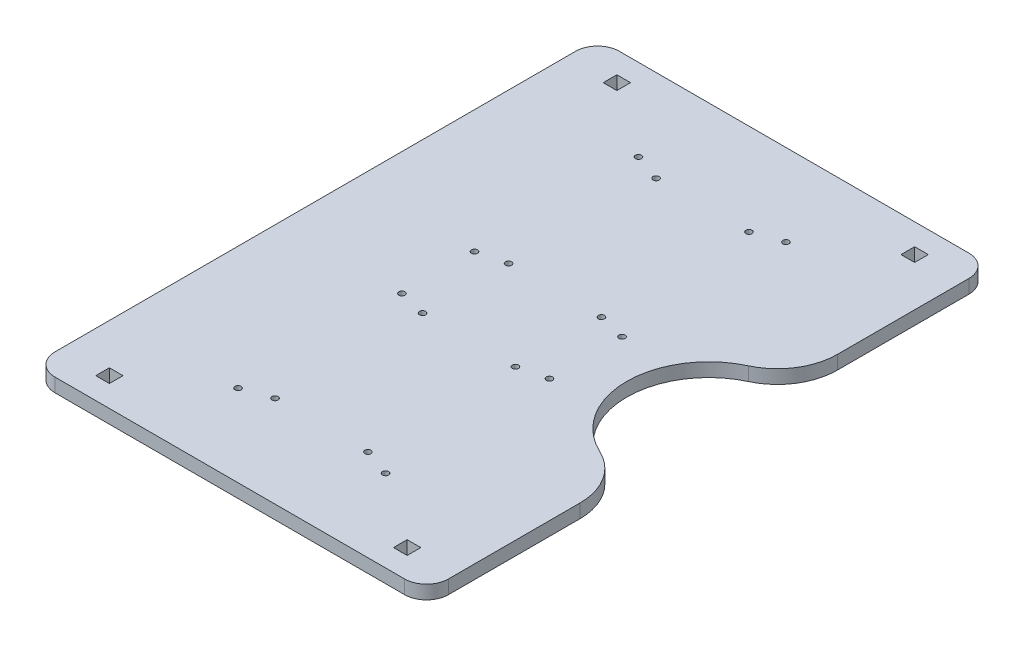
SolidWorks part; units mm, degrees
ref_plane "Front Plane" through (0, 0, 0) normal (0, 0, 1) x (1, 0, 0)
ref_plane "Top Plane" through (0, 0, 0) normal (0, 1, 0) x (1, 0, 0)
ref_plane "Right Plane" through (0, 0, 0) normal (1, 0, 0) x (0, 0, -1)
sketch "Sketch3" plane through (0, 0, 0) normal (0, 1, 0) x (1, 0, 0)
  line L4 (182.88, 0) -> (0, 0)
  line L5 (91.44, 262.3393) -> (91.44, 0) construction
  line L6 (19.05, 16.3877) -> (25.4, 16.3877)
  line L7 (19.05, 16.3877) -> (19.05, 10.0377)
  line L8 (19.05, 10.0377) -> (25.4, 10.0377)
  line L9 (25.4, 16.3877) -> (25.4, 10.0377)
  line L10 (163.83, 10.0377) -> (157.48, 10.0377)
  line L11 (157.48, 16.3877) -> (157.48, 10.0377)
  line L12 (163.83, 16.3877) -> (157.48, 16.3877)
  line L13 (163.83, 16.3877) -> (163.83, 10.0377)
  line L14 (0, 0) -> (0, 262.3393)
  line L15 (0, 262.3393) -> (182.88, 262.3393)
  line L16 (182.88, 262.3393) -> (182.88, 169.2696)
  line L17 (0, 131.1696) -> (152.4, 131.1696) construction
  line L18 (163.83, 245.9515) -> (163.83, 252.3015)
  line L19 (163.83, 245.9515) -> (157.48, 245.9515)
  line L20 (157.48, 245.9515) -> (157.48, 252.3015)
  line L21 (163.83, 252.3015) -> (157.48, 252.3015)
  line L22 (19.05, 252.3015) -> (25.4, 252.3015)
  line L23 (25.4, 245.9515) -> (25.4, 252.3015)
  line L24 (19.05, 245.9515) -> (25.4, 245.9515)
  line L25 (19.05, 245.9515) -> (19.05, 252.3015)
  line L26 (182.88, 93.0696) -> (182.88, 0)
  circle A6 centre (57.15, 38.1) radius 1.4224
  circle A7 centre (57.15, 114.3) radius 1.4224
  circle A8 centre (125.73, 114.3) radius 1.4224
  circle A9 centre (125.73, 38.1) radius 1.4224
  circle A10 centre (69.85, 151.1577) radius 1.4224
  circle A11 centre (69.85, 219.7377) radius 1.4224
  circle A12 centre (113.03, 151.1577) radius 1.4224
  circle A13 centre (113.03, 219.7377) radius 1.4224
  circle A14 centre (113.03, 42.6016) radius 1.4224
  circle A15 centre (113.03, 111.1816) radius 1.4224
  circle A16 centre (69.85, 111.1816) radius 1.4224
  circle A17 centre (69.85, 42.6016) radius 1.4224
  circle A18 centre (125.73, 148.0393) radius 1.4224
  circle A19 centre (125.73, 224.2393) radius 1.4224
  circle A20 centre (57.15, 224.2393) radius 1.4224
  circle A21 centre (57.15, 148.0393) radius 1.4224
  arc A22 (182.88, 169.2696) -> (182.88, 93.0696) centre (182.88, 131.1696) ccw
  dimension "D2" = 19.05
  dimension "D3" = 0
  dimension "D10" = 38.1
  dimension "D13" = 68.58
  dimension "D4" = 19.05
  dimension "D5" = 182.88
  dimension "D6" = 6.35
  dimension "D7" = 6.35
  dimension "D11" = 76.2
  dimension "D12" = 68.58
  dimension "D14" = 43.18
extrude "Boss-Extrude1" add sketch "Sketch3" along normal blind 6.35
fillet "Fillet1" radius 10.16 4 edges at (0, 3.175, 0) (0, 3.175, -262.3393) (182.88, 3.175, -262.3393) (182.88, 3.175, 0)
fillet "Fillet2" radius 27.94 2 edges at (182.88, 3.175, -169.2696) (182.88, 3.175, -93.0696)
